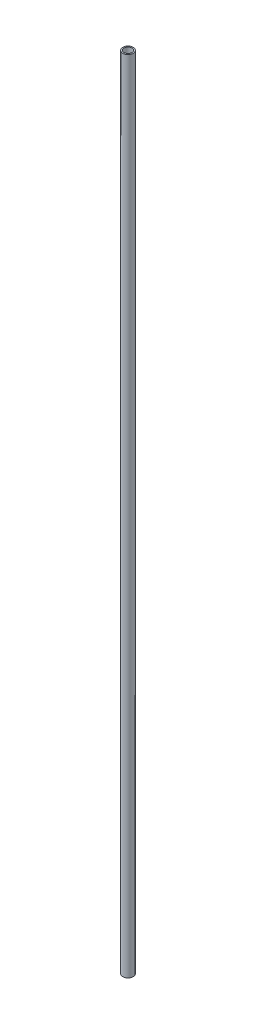
SolidWorks part; units mm, degrees
ref_plane "Front Plane" through (0, 0, 0) normal (0, 0, 1) x (1, 0, 0)
ref_plane "Top Plane" through (0, 0, 0) normal (0, 1, 0) x (1, 0, 0)
ref_plane "Right Plane" through (0, 0, 0) normal (1, 0, 0) x (0, 0, -1)
sketch "Sketch1" plane through (0, 0, 0) normal (0, 0, 1) x (1, 0, 0)
  line L0 (0, 0) -> (0, 610)
  point P6 (0, 610)
  dimension "D1" = 610
sketch "Sketch2" plane through (0, 0, 0) normal (0, 1, 0) x (1, 0, 0)
  circle A0 centre (0, 0) radius 4
  circle A1 centre (0, 0) radius 3
  dimension "D1" = 6
  dimension "D2" = 8
sweep "Sweep1" add profiles "Sketch2" path "Sketch1"
